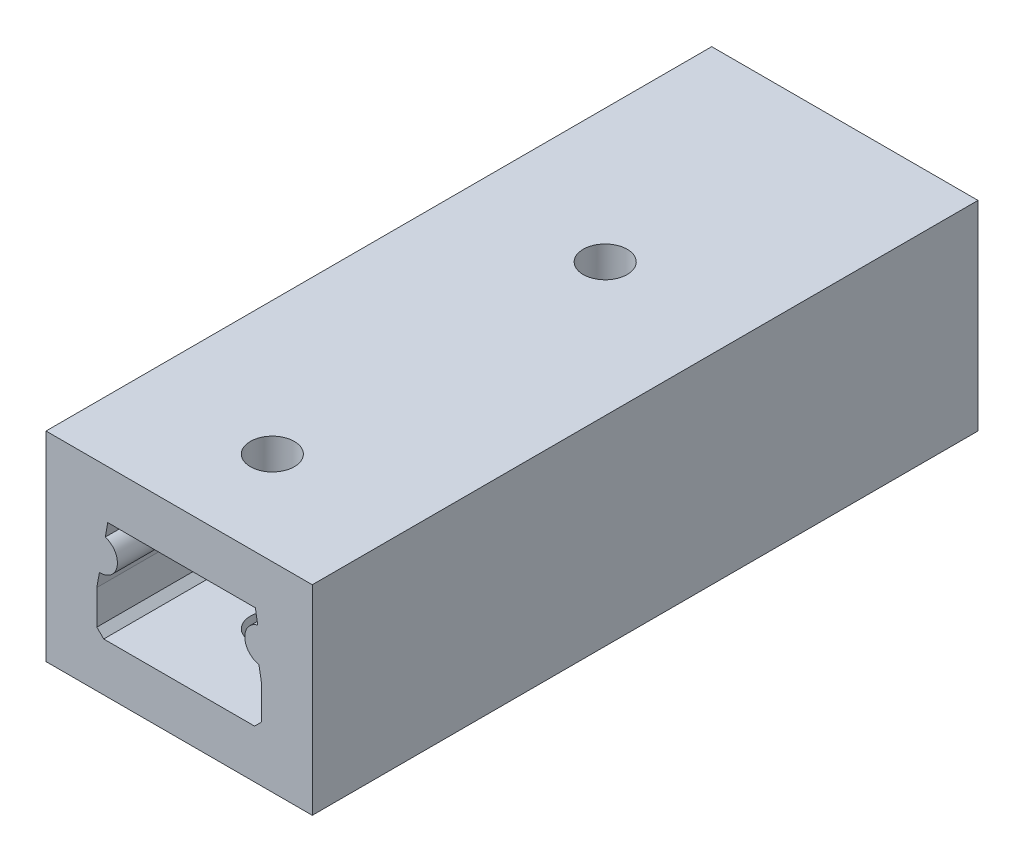
SolidWorks part; units mm, degrees
ref_plane "Front Plane" through (0, 0, 0) normal (0, 0, 1) x (1, 0, 0)
ref_plane "Top Plane" through (0, 0, 0) normal (0, 1, 0) x (1, 0, 0)
ref_plane "Right Plane" through (0, 0, 0) normal (1, 0, 0) x (0, 0, -1)
sketch "Sketch2" plane through (0, 0, 0) normal (0, 0, 1) x (1, 0, 0)
  line L0 (0.18, -0.3375) -> (0.18, 7.6125) construction
  line L2 (-10, -3.75) -> (10, -3.75)
  line L3 (-10, -3.75) -> (-10, 11.25)
  line L4 (-10, 11.25) -> (10, 11.25)
  line L5 (10, -3.75) -> (10, 11.25)
  line L6 (-10, -3.75) -> (10, 11.25) construction
  line L7 (-10, 11.25) -> (10, -3.75) construction
  line L20 (6.18, 0.4025) -> (6.18, 2.9775)
  line L21 (6.18, 2.9775) -> (5.989, 4.0607)
  line L22 (5.9052, 6.5775) -> (5.7227, 7.6125)
  line L23 (5.7227, 7.6125) -> (-5.3627, 7.6125)
  line L24 (-5.3627, 7.6125) -> (-5.5452, 6.5775)
  line L25 (-5.989, 4.0607) -> (-6.18, 2.9775)
  line L26 (-6.18, 2.9775) -> (-6.18, 0.4025)
  line L27 (-6.18, 0.4025) -> (-5.665, -0.1125)
  line L28 (-5.665, -0.1125) -> (5.665, -0.1125)
  line L29 (5.665, -0.1125) -> (6.18, 0.4025)
  arc A4 (5.9052, 6.5775) -> (5.989, 4.0607) centre (6.216, 5.3281) ccw
  arc A5 (-5.989, 4.0607) -> (-5.5452, 6.5775) centre (-5.9225, 5.3465) ccw
  point P9 (0.18, 3.6375)
  dimension "D1" = 15
  dimension "D2" = 20
  dimension "D3" = 3.75
  dimension "D4" = 6
extrude "Boss-Extrude1" add sketch "Sketch2" along normal blind 50
sketch "Sketch3" plane through (0, 11.25, 0) normal (0, 1, 0) x (1, 0, 0)
  line L0 (0, 0) -> (0, -52.6275) construction
  line L1 (10, 0) -> (-10, 0) construction
  circle A0 centre (0, -18) radius 1.65
  circle A1 centre (0, -43) radius 1.65
  point P8 (0, 0)
  point P11 (1.3667, -2.0585)
  point P12 (2.5382, -0.7568)
  dimension "D1" = 3.3
  dimension "D3" = 18
  dimension "D2" = 25
extrude "Cut-Extrude1" cut sketch "Sketch3" against normal through all
